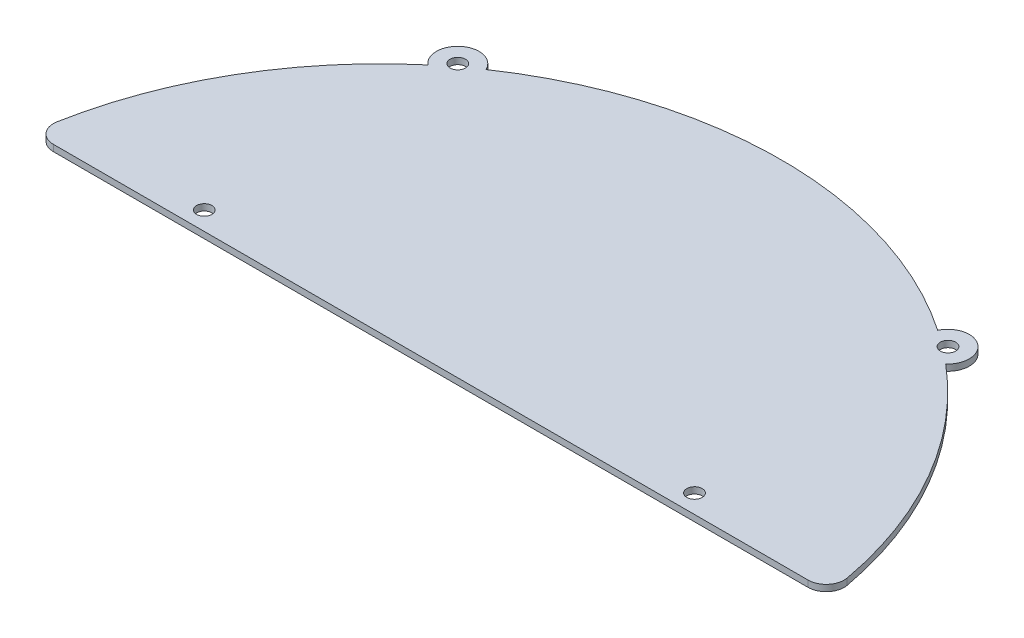
SolidWorks part; units mm, degrees
ref_plane "Plan de face" through (0, 0, 0) normal (0, 0, 1) x (1, 0, 0)
ref_plane "Plan de dessus" through (0, 0, 0) normal (0, 1, 0) x (1, 0, 0)
ref_plane "Plan de droite" through (0, 0, 0) normal (1, 0, 0) x (0, 0, -1)
sketch "Esquisse1" plane through (0, 0, 0) normal (0, 1, 0) x (1, 0, 0)
  line L0 (-95.25, 0) -> (95.25, 0)
  line L1 (0, 0) -> (0, 83.82) construction
  arc A0 (-95.25, 0) -> (95.25, 0) centre (0, -12.2093) cw
  point P2 (0, 0)
  dimension "D1" = 190.5
  dimension "D2" = 83.82
extrude "Boss.-Extru.1" add sketch "Esquisse1" along normal blind 1.524 contours A0 L0
fillet "Congé1" radius 4.318 2 edges at (-95.25, 0.762, 0) (95.25, 0.762, 0)
sketch "Esquisse2" plane through (0, 1.524, 0) normal (0, 1, 0) x (1, 0, 0)
  line L0 (53.9977, 67.2002) -> (61.9104, 61.1987) construction
  line L1 (53.9977, 67.2002) -> (62.1105, 61.0294)
  line L2 (93.5268, 1.5535) -> (58.6018, 1.5535) construction
  line L3 (58.6018, 1.5535) -> (58.6018, 65.0535) construction
  line L4 (0, 0) -> (0, 107.9902) construction
  line L5 (-61.9104, 61.1987) -> (-53.9977, 67.2002)
  arc A1 (90.2098, 0) -> (94.4571, 5.0961) centre (90.2098, 4.318) ccw construction
  circle A2 centre (58.6018, 65.0535) radius 1.8415
  arc A3 (61.9104, 61.1987) -> (53.9977, 67.2002) centre (58.6018, 65.0535) ccw
  arc A4 (94.4571, 5.0961) -> (-94.4571, 5.0961) centre (0, -12.2093) ccw construction
  circle A5 centre (-58.6018, 65.0535) radius 1.8415
  arc A6 (-61.9104, 61.1987) -> (-53.9977, 67.2002) centre (-58.6018, 65.0535) cw
  arc M9 (94.4571, 5.0961) -> (-94.4571, 5.0961) centre (0, -12.2093) ccw
  dimension "D1" = 3.683
  dimension "D2" = 10.16
  dimension "D3" = 34.925
  dimension "D4" = 63.5
extrude "Boss.-Extru.3" add sketch "Esquisse2" against normal up to surface (1.524 mm away) contours A3 A2 M9 | A6 A5 M9
sketch "Esquisse3" plane through (0, 1.524, 0) normal (0, 1, 0) x (1, 0, 0)
  line L0 (0, 83.82) -> (0, 0) construction
  line L1 (58.6018, 0) -> (58.6018, 4.445) construction
  line L2 (-90.2098, 0) -> (90.2098, 0) construction
  circle A0 centre (58.6018, 65.0535) radius 1.8415
  arc A1 (53.9977, 67.2002) -> (-53.9977, 67.2002) centre (0, -12.2093) ccw construction
  circle A2 centre (-58.6018, 65.0535) radius 1.8415
  circle A3 centre (58.6018, 4.445) radius 1.8415
  circle A4 centre (-58.6018, 4.445) radius 1.8415
  dimension "D2" = 3.683
  dimension "D3" = 3.683
  dimension "D1" = 4.445
extrude "Enlèv. mat.-Extru.1" cut sketch "Esquisse3" against normal through all
